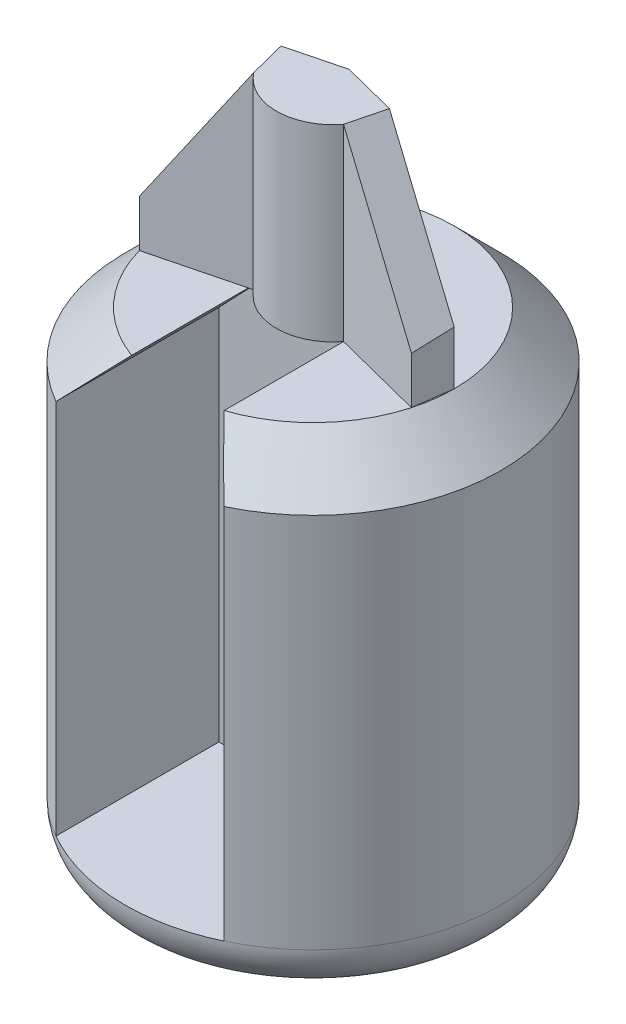
SolidWorks part; units mm, degrees
ref_plane "Front Plane" through (0, 0, 0) normal (0, 0, 1) x (1, 0, 0)
ref_plane "Top Plane" through (0, 0, 0) normal (0, 1, 0) x (1, 0, 0)
ref_plane "Right Plane" through (0, 0, 0) normal (1, 0, 0) x (0, 0, -1)
sketch "Sketch1" plane through (0, 0, 0) normal (0, 1, 0) x (1, 0, 0)
  circle A0 centre (0, 0) radius 50.8
  dimension "D1" = 101.6
extrude "Boss-Extrude1" add sketch "Sketch1" along normal blind 127
fillet "Fillet2" radius 12.7 1 edges at (0, 0, 50.8)
chamfer "Chamfer1" distance 12.7 angle 45 1 edges at (0, 127, 50.8)
sketch "Sketch2" plane through (0, 127, 0) normal (0, 1, 0) x (1, 0, 0)
  line L0 (0, 49.017) -> (0, -58.836) construction
  line L1 (0, 9.7255) -> (-38.1, 0)
  line L2 (-38.1, 0) -> (-36.7204, -10.16)
  line L3 (-36.7204, -10.16) -> (0, -0.7866)
  line L4 (0, -0.7866) -> (36.7204, -10.16)
  line L5 (36.7204, -10.16) -> (38.1, 0)
  line L6 (38.1, 0) -> (0, 9.7255)
  circle A0 centre (0, 0) radius 38.1 construction
  dimension "D1" = 10.16
  dimension "D2" = 10.16
  dimension "D3" = 38.1
  dimension "D4" = 38.1
  dimension "D5" = 36.7204
  dimension "D6" = 107.853
  dimension "D7" = 151.361
  dimension "D8" = 151.361
  dimension "D9" = 83.413
  dimension "D10" = 83.413
  dimension "D11" = 83.413
  dimension "D12" = 39.3217
extrude "Boss-Extrude2" add sketch "Sketch2" along normal blind 50.8
sketch "Sketch3" plane through (0.1885, 0, 0.7385) normal (0.2473, 0, 0.9689) x (0.9689, 0, -0.2473)
  line L0 (-38.0924, 139.7) -> (-38.0924, 177.8)
  line L1 (-38.0924, 177.8) -> (-38.0924, 127) construction
  line L2 (-38.0924, 177.8) -> (-12.6924, 177.8)
  line L3 (-38.0924, 177.8) -> (-0.1946, 177.8) construction
  line L4 (-12.6924, 177.8) -> (-38.0924, 139.7)
  dimension "D1" = 38.1
  dimension "D2" = 25.4
extrude "Cut-Extrude2" cut sketch "Sketch3" against normal through all
sketch "Sketch4" plane through (-0.1885, 0, 0.7385) normal (-0.2473, 0, 0.9689) x (0.9689, 0, 0.2473)
  line L0 (12.6924, 177.8) -> (38.0924, 177.8)
  line L1 (0.1946, 177.8) -> (38.0924, 177.8) construction
  line L2 (38.0924, 177.8) -> (38.0924, 139.7)
  line L3 (38.0924, 177.8) -> (38.0924, 127) construction
  line L4 (38.0924, 139.7) -> (12.6924, 177.8)
  dimension "D1" = 25.4
  dimension "D2" = 38.1
extrude "Cut-Extrude3" cut sketch "Sketch4" against normal through all contours L4 L0 L2
sketch "Sketch5" plane through (0, 127, 0) normal (0, 1, 0) x (1, 0, 0)
  line L0 (-12.1095, -3.8778) -> (0, -0.7866)
  line L1 (0, -0.7866) -> (12.1095, -3.8778)
  arc A0 (-12.1095, -3.8778) -> (12.1095, -3.8778) centre (0, 5.3752) ccw
  dimension "D1" = 15.24
extrude "Boss-Extrude3" add sketch "Sketch5" along normal blind 50.8
sketch "Sketch6" plane through (0, 0, 0) normal (0, 0, 1) x (1, 0, 0)
  line L0 (-13.2905, 127) -> (-25.4, 114.3)
  line L1 (36.7204, 127) -> (-36.7204, 127) construction
  line L2 (-50.8, 114.3) -> (50.8, 114.3) construction
  line L3 (-25.4, 114.3) -> (-25.4, 12.7)
  line L4 (-25.4, 12.7) -> (21.82, 12.7)
  line L5 (21.82, 12.7) -> (21.82, 114.3)
  line L6 (21.82, 114.3) -> (12.1095, 127)
  line L7 (12.1095, 127) -> (-13.2905, 127)
  line L8 (-50.8, 114.3) -> (-50.8, 12.7) construction
  line L9 (50.8, 12.7) -> (50.8, 114.3) construction
  dimension "D1" = 101.6
  dimension "D2" = 25.4
  dimension "D3" = 28.98
  dimension "D4" = 25.4
extrude "Cut-Extrude4" cut sketch "Sketch6" along normal up to next contours L7 L0 L3 L4 L5 L6
